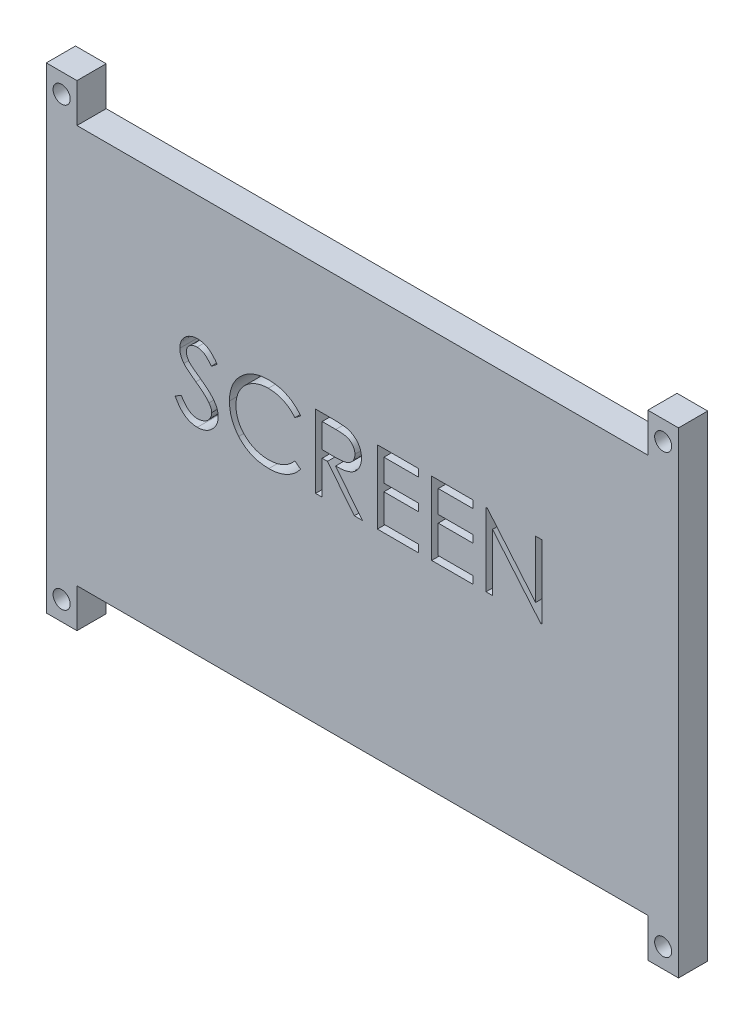
SolidWorks part; units mm, degrees
ref_plane "Front Plane" through (0, 0, 0) normal (0, 0, 1) x (1, 0, 0)
ref_plane "Top Plane" through (0, 0, 0) normal (0, 1, 0) x (1, 0, 0)
ref_plane "Right Plane" through (0, 0, 0) normal (1, 0, 0) x (0, 0, -1)
sketch "Sketch1" plane through (0, 0, 0) normal (0, 0, 1) x (1, 0, 0)
  line L1 (-134.2916, 98.9404) -> (30.6084, 98.9404)
  line L2 (-134.2916, 98.9404) -> (-134.2916, -25.3296)
  line L3 (-134.2916, -25.3296) -> (30.6084, -25.3296)
  line L4 (30.6084, 98.9404) -> (30.6084, -25.3296)
  dimension "D1" = 164.9
  dimension "D2" = 124.27
extrude "Boss-Extrude1" add sketch "Sketch1" along normal blind 7.62
sketch "Sketch2" plane through (0, 0, 7.62) normal (0, 0, 1) x (1, 0, 0)
  line L0 (-134.2916, 36.8054) -> (30.6084, 36.8054) construction
  line L1 (-134.2916, 98.9404) -> (-134.2916, -25.3296) construction
  line L2 (30.6084, -25.3296) -> (30.6084, 98.9404) construction
  text T0 "SCREEN" font "Century Gothic" height in points 72
extrude "Cut-Extrude1" cut sketch "Sketch2" against normal through all
sketch "Sketch3" plane through (0, 0, 7.62) normal (0, 0, 1) x (1, 0, 0)
  line L0 (-134.2916, 98.9404) -> (-126.2916, 98.9404)
  line L1 (30.6084, 98.9404) -> (-134.2916, 98.9404) construction
  line L2 (30.6084, 98.9404) -> (22.6084, 98.9404)
  line L3 (-126.2916, 98.9404) -> (-126.2916, 88.7854)
  line L4 (22.6084, 98.9404) -> (22.6084, 88.7854)
  line L5 (-134.2916, -25.3296) -> (-126.2916, -25.3296)
  line L6 (-134.2916, -25.3296) -> (30.6084, -25.3296) construction
  line L7 (30.6084, -25.3296) -> (22.6084, -25.3296)
  line L8 (30.6084, -25.3296) -> (30.6084, -15.1746)
  line L9 (30.6084, -25.3296) -> (30.6084, 98.9404) construction
  line L10 (-134.2916, -25.3296) -> (-134.2916, -15.1746)
  line L11 (-134.2916, 98.9404) -> (-134.2916, -25.3296) construction
  line L13 (-126.2916, 88.7854) -> (22.6084, 88.7854)
  line L14 (-126.2916, 88.7854) -> (-126.2916, 98.9404)
  line L15 (-126.2916, 98.9404) -> (22.6084, 98.9404)
  line L16 (22.6084, 88.7854) -> (22.6084, 98.9404)
  line L17 (-126.2916, -25.3296) -> (22.6084, -25.3296)
  line L18 (-126.2916, -25.3296) -> (-126.2916, -15.1746)
  line L19 (-126.2916, -15.1746) -> (22.6084, -15.1746)
  line L20 (22.6084, -25.3296) -> (22.6084, -15.1746)
  dimension "D1" = 8
  dimension "D2" = 8
  dimension "D3" = 10.155
  dimension "D4" = 10.155
extrude "Cut-Extrude2" cut sketch "Sketch3" against normal through all contours L17 L20 L19 L18 | L15 L3 L13 L4
sketch "Sketch5" plane through (0, 0, 7.62) normal (0, 0, 1) x (1, 0, 0)
  line L0 (26.6084, 98.9404) -> (26.6084, 88.5455)
  line L1 (30.6084, 98.9404) -> (22.6084, 98.9404) construction
  line L2 (22.6084, 93.8629) -> (30.6084, 93.8629)
  line L3 (22.6084, 98.9404) -> (22.6084, 88.7854) construction
  line L4 (30.6084, -25.3296) -> (30.6084, 98.9404) construction
  line L5 (26.6084, -25.3296) -> (26.6084, -14.7406)
  line L6 (22.6084, -25.3296) -> (30.6084, -25.3296) construction
  line L7 (22.6084, -20.2521) -> (30.6084, -20.2521)
  line L8 (22.6084, -25.3296) -> (22.6084, -15.1746) construction
  line L9 (-130.2916, -25.3296) -> (-130.2916, -14.7406)
  line L10 (-134.2916, -25.3296) -> (-126.2916, -25.3296) construction
  line L11 (-126.2916, -20.2521) -> (-134.2916, -20.2521)
  line L12 (-126.2916, -25.3296) -> (-126.2916, -15.1746) construction
  line L13 (-134.2916, 98.9404) -> (-134.2916, -25.3296) construction
  line L14 (-130.2916, 98.9404) -> (-130.2916, 87.6168)
  line L15 (-126.2916, 98.9404) -> (-134.2916, 98.9404) construction
  line L16 (-126.2916, 93.8629) -> (-134.2916, 93.8629)
  line L17 (-126.2916, 98.9404) -> (-126.2916, 88.7854) construction
  circle A0 centre (-130.2916, 93.8629) radius 2.2397
  circle A1 centre (26.6084, 93.8629) radius 2.2234
  circle A2 centre (26.6084, -20.2521) radius 2.2222
  circle A3 centre (-130.2916, -20.2521) radius 2.2235
extrude "Cut-Extrude3" cut sketch "Sketch5" against normal through all contours L11 A3 L9 | L9 A3 L11 | L11 A3 L9 | L9 A3 L11 | L16 A0 L14 | L14 A0 L16 | L16 A0 L14 | L14 A0 L16 | L0 A1 L2 | L2 A1 L0 | L0 A1 L2 | L2 A1 L0 | L5 A2 L7 | L7 A2 L5 | L5 A2 L7 | L7 A2 L5
